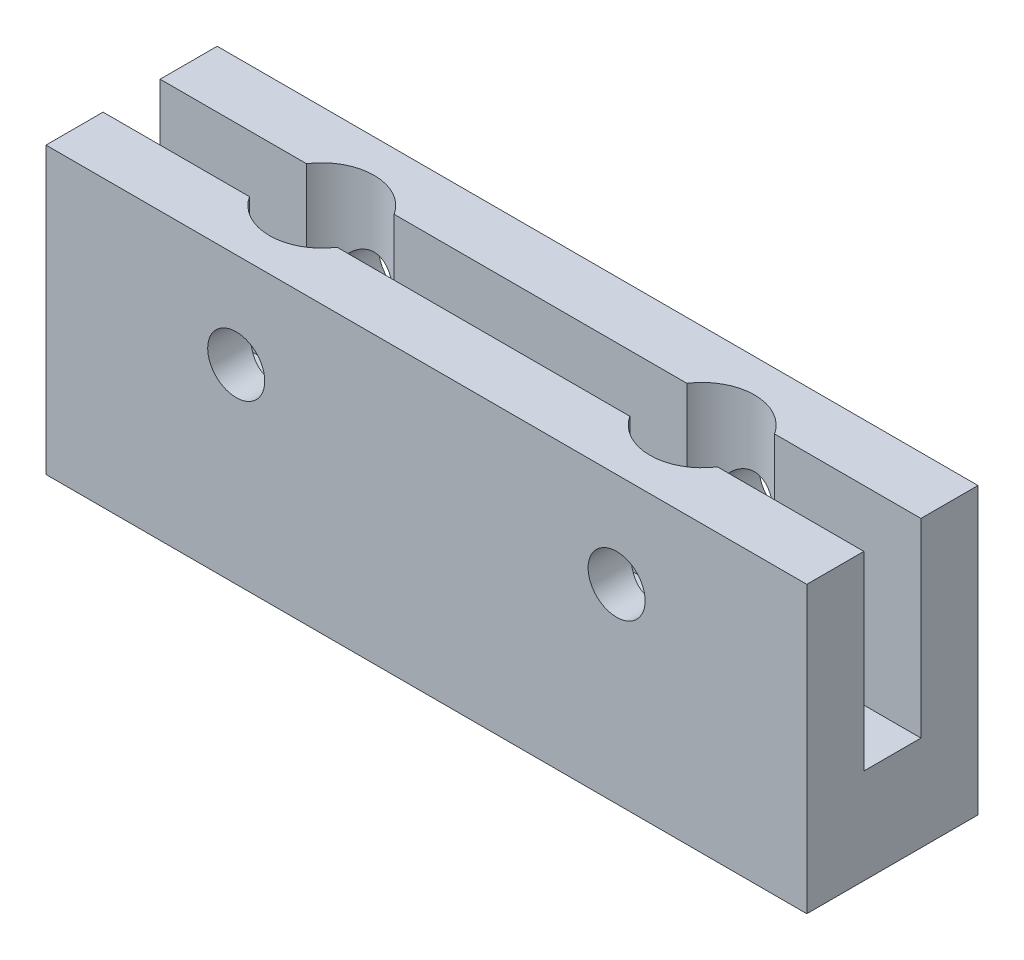
SolidWorks part; units mm, degrees
ref_plane "Front Plane" through (0, 0, 0) normal (0, 0, 1) x (1, 0, 0)
ref_plane "Top Plane" through (0, 0, 0) normal (0, 1, 0) x (1, 0, 0)
ref_plane "Right Plane" through (0, 0, 0) normal (1, 0, 0) x (0, 0, -1)
sketch "Sketch1" plane through (0, 0, 0) normal (0, 1, 0) x (1, 0, 0)
  line L1 (-20, 4.5) -> (20, 4.5)
  line L2 (-20, 4.5) -> (-20, -4.5)
  line L3 (-20, -4.5) -> (20, -4.5)
  line L4 (20, 4.5) -> (20, -4.5)
  line L5 (-20, 4.5) -> (20, -4.5) construction
  line L6 (-20, -4.5) -> (20, 4.5) construction
  point P0 (0, 0)
extrude "Boss-Extrude1" add sketch "Sketch1" along normal blind 5
sketch "Sketch2" plane through (0, 5, 0) normal (0, 1, 0) x (1, 0, 0)
  line L0 (-20, 4.5) -> (-20, 1.5)
  line L1 (-20, 4.5) -> (-20, -4.5) construction
  line L2 (-20, 1.5) -> (20, 1.5)
  line L3 (20, -4.5) -> (20, 4.5) construction
  line L4 (20, 1.5) -> (20, 4.5)
  line L5 (20, 4.5) -> (-20, 4.5)
  line L6 (-5.5, 0) -> (5.5, 0) construction
  line L7 (20, -1.5) -> (20, -4.5)
  line L8 (-20, -1.5) -> (20, -1.5)
  line L9 (-20, -4.5) -> (-20, -1.5)
  line L10 (20, -4.5) -> (-20, -4.5)
  line L11 (0, 0) -> (-20, 0) construction
extrude "Boss-Extrude4" add sketch "Sketch2" along normal blind 10
sketch "Sketch4" plane through (0, 15, 0) normal (0, 1, 0) x (1, 0, 0)
  line L0 (0, 0) -> (-20, 0) construction
  line L1 (-20, 1.5) -> (-20, -1.5) construction
  line L2 (0, -2.75) -> (0, 2.75) construction
  circle A0 centre (-10, 0) radius 2.75
  circle A1 centre (10, 0) radius 2.75
extrude "Cut-Extrude5" cut sketch "Sketch4" against normal blind 12.5 and the other way through all
sketch "Sketch5" plane through (0, 2.5, 0) normal (0, 1, 0) x (1, 0, 0)
  circle A0 centre (-10, 0) radius 1.5
  circle A1 centre (10, 0) radius 1.5
extrude "Cut-Extrude6" cut sketch "Sketch5" against normal through all both
sketch "Sketch6" plane through (0, 0, 4.5) normal (0, 0, 1) x (1, 0, 0)
  circle A0 centre (-10, 10) radius 1.5
  circle A1 centre (10, 10) radius 1.5
extrude "Cut-Extrude7" cut sketch "Sketch6" against normal through all both and the other way through all
